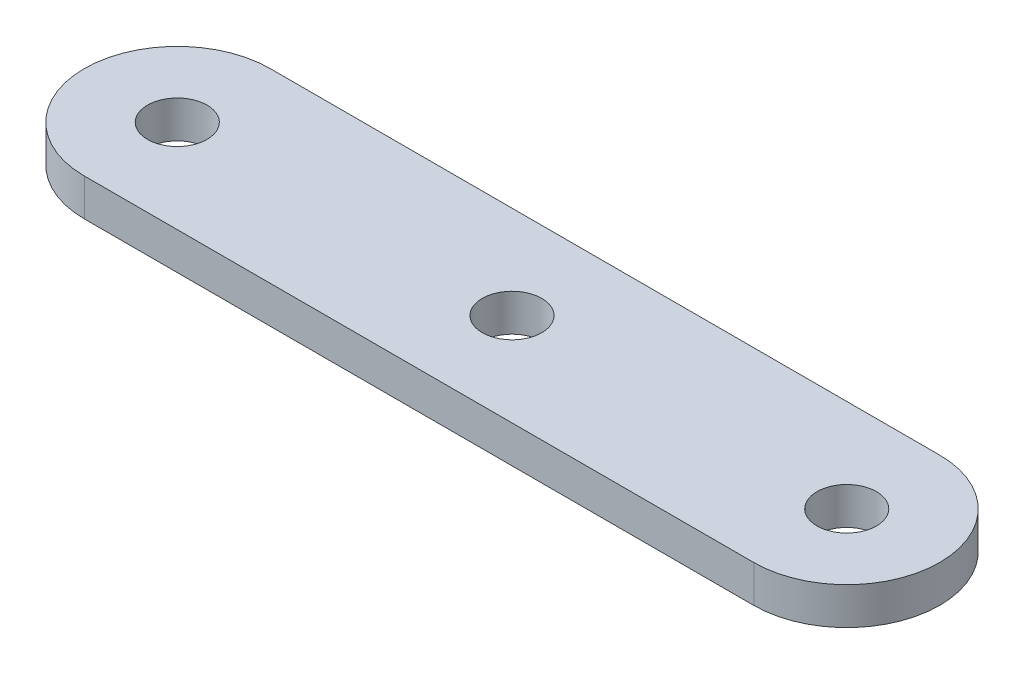
SolidWorks part; units mm, degrees
ref_plane "Front Plane" through (0, 0, 0) normal (0, 0, 1) x (1, 0, 0)
ref_plane "Top Plane" through (0, 0, 0) normal (0, 1, 0) x (1, 0, 0)
ref_plane "Right Plane" through (0, 0, 0) normal (1, 0, 0) x (0, 0, -1)
sketch "Sketch1" plane through (0, 0, 0) normal (0, 1, 0) x (1, 0, 0)
  line L0 (-22.4891, 0) -> (22.0986, 0) construction
  line L1 (0, 9.3089) -> (0, -7.5188) construction
  line L2 (-18, 0) -> (18, 0) construction
  line L3 (-18, 5) -> (18, 5)
  line L4 (-18, -5) -> (18, -5)
  circle A0 centre (18, 0) radius 1.6
  circle A1 centre (-18, 0) radius 1.6
  arc A2 (-18, 5) -> (-18, -5) centre (-18, 0) ccw
  arc A3 (18, -5) -> (18, 5) centre (18, 0) ccw
  circle A4 centre (0, 0) radius 1.6
  point P9 (0, 0)
  dimension "D1" = 3.2
  dimension "D3" = 5
  dimension "D4" = 3.2
  dimension "D2" = 18
extrude "Boss-Extrude1" add sketch "Sketch1" along normal blind 2
